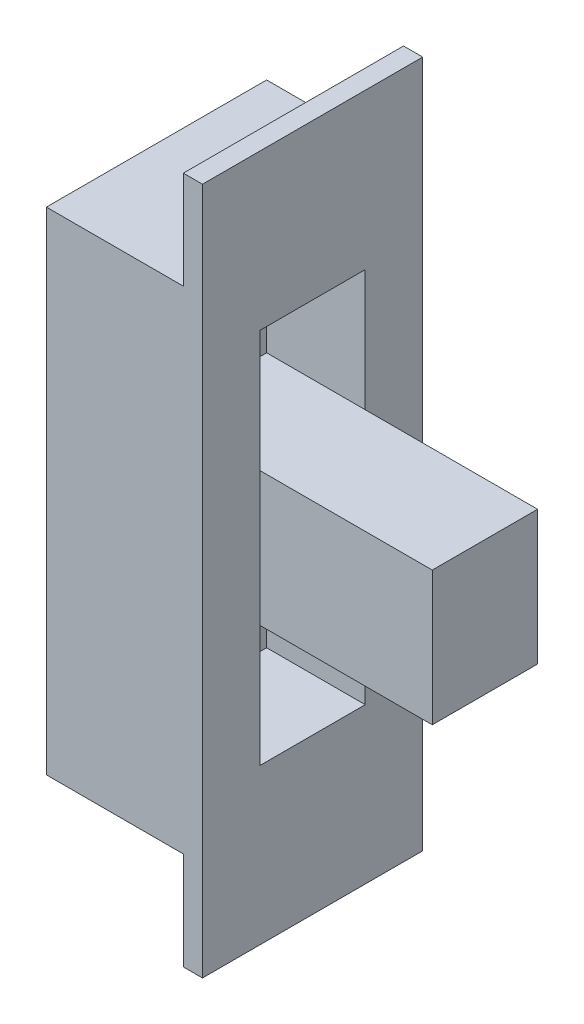
SolidWorks part; units mm, degrees
ref_plane "Plane1" through (0, 0, 0) normal (0, 0, 1) x (1, 0, 0)
ref_plane "Plane2" through (0, 0, 0) normal (0, 1, 0) x (1, 0, 0)
ref_plane "Plane3" through (0, 0, 0) normal (1, 0, 0) x (0, 0, -1)
other "Configuration Table"
sketch "Sketch2" plane through (0, 0, 0) normal (0, 0, 1) x (1, 0, 0)
  line L0 (-7.2426, 56.73) -> (-7.2426, 20.83)
  line L1 (-8.2426, 20.83) -> (-8.2426, 56.73)
  line L8 (-7.2426, 56.73) -> (-14.2426, 56.73) construction
  line L9 (-7.2426, 56.73) -> (-8.2426, 56.73)
  line L10 (-14.2426, 20.83) -> (-7.2426, 20.83) construction
  line L11 (-8.2426, 20.83) -> (-7.2426, 20.83)
extrude "Base-Extrude" add sketch "Sketch2" along normal blind 11.5
sketch "Sketch3" plane through (-8.2426, 0, 0) normal (-1, 0, 0) x (0, 0, 1)
  line L2 (0, 51.6191) -> (6.64, 51.6191) construction
  line L3 (0, 51.6191) -> (11.5, 51.6191)
  line L4 (0, 25.9409) -> (11.5, 25.9409)
  line L5 (0, 51.6191) -> (0, 25.9409)
  line L6 (11.5, 20.83) -> (11.5, 56.73) construction
  line L7 (11.5, 25.9409) -> (11.5, 51.6191)
extrude "Boss-Extrude1" add sketch "Sketch3" along normal blind 7.15
sketch "Sketch4" plane through (-7.2426, 0, 0) normal (1, 0, 0) x (0, 0, -1)
  line L4 (-8.5, 28.9409) -> (-8.5, 48.6191)
  line L5 (-8.5, 48.6191) -> (-3, 48.6191)
  line L6 (-3, 48.6191) -> (-3, 28.9409)
  line L7 (-3, 28.9409) -> (-8.5, 28.9409)
  line L8 (-8.5, 28.9409) -> (-8.5, 48.6191)
  line L9 (-8.5, 48.6191) -> (-3, 48.6191)
  line L10 (-3, 48.6191) -> (-3, 28.9409)
  line L11 (-3, 28.9409) -> (-8.5, 28.9409)
  dimension "D1" = 3
extrude "Cut-Extrude1" cut sketch "Sketch4" against normal offset from surface (5.15 mm away) 3 up to face at (-15.3926, 38.78, 5.75)
sketch "Sketch5" plane through (-12.3926, 0, 0) normal (1, 0, 0) x (0, 0, -1)
  line L0 (-8.5, 42.2794) -> (-3, 42.2794)
  line L1 (-8.5, 35.2794) -> (-3, 35.2794)
  line L4 (-3, 28.9409) -> (-3, 48.6191)
  line L5 (-3, 48.6191) -> (-8.5, 48.6191)
  line L6 (-8.5, 48.6191) -> (-8.5, 28.9409)
  line L7 (-8.5, 28.9409) -> (-3, 28.9409)
  line L8 (-3, 35.2794) -> (-3, 42.2794)
  line L10 (-8.5, 42.2794) -> (-8.5, 35.2794)
  dimension "D2" = 7
  dimension "D1" = 0
extrude "Boss-Extrude3" add sketch "Sketch5" along normal offset from surface (14.15 mm away) 9 up to face at (-7.2426, 38.78, 5.75) offset beyond the face yes
